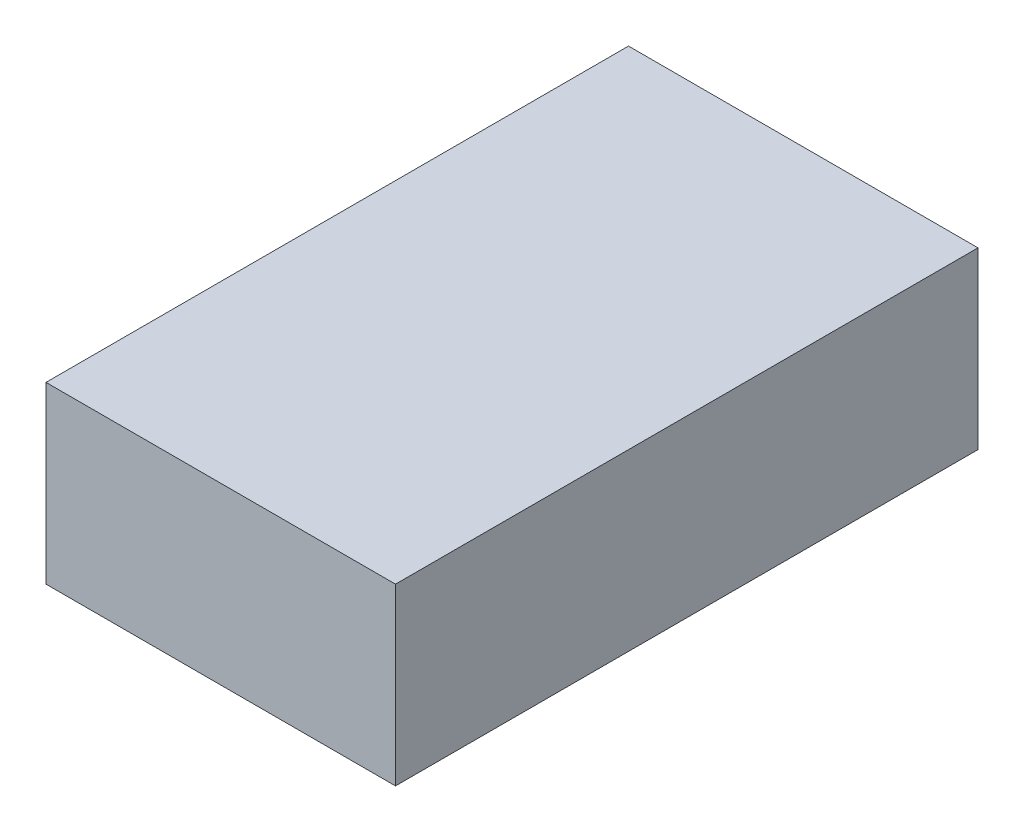
SolidWorks part; units mm, degrees
ref_plane "Alzado" through (0, 0, 0) normal (0, 0, 1) x (1, 0, 0)
ref_plane "Planta" through (0, 0, 0) normal (0, 1, 0) x (1, 0, 0)
ref_plane "Vista lateral" through (0, 0, 0) normal (1, 0, 0) x (0, 0, -1)
sketch "Croquis1" plane through (0, 0, 0) normal (0, 0, 1) x (1, 0, 0)
  line L1 (-10.082, 1.7951) -> (-4.082, 1.7951)
  line L2 (-10.082, 1.7951) -> (-10.082, -1.2049)
  line L3 (-10.082, -1.2049) -> (-4.082, -1.2049)
  line L4 (-4.082, 1.7951) -> (-4.082, -1.2049)
  dimension "D1" = 6
  dimension "D2" = 3
extrude "Saliente-Extruir1" add sketch "Croquis1" along normal blind 10
